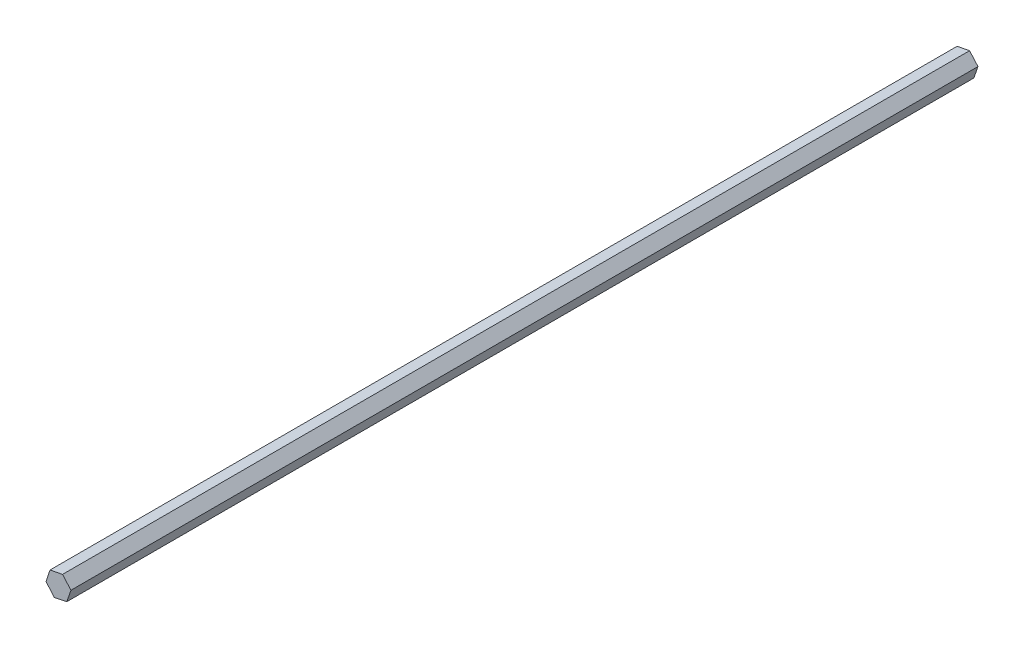
SolidWorks part; units mm, degrees
material "6061 Alloy"
ref_plane "Front Plane" through (0, 0, 0) normal (0, 0, 1) x (1, 0, 0)
ref_plane "Top Plane" through (0, 0, 0) normal (0, 1, 0) x (1, 0, 0)
ref_plane "Right Plane" through (0, 0, 0) normal (1, 0, 0) x (0, 0, -1)
ref_plane "Plane1" through (0, 0, -228.6) normal (0, 0, -1) x (-1, 0, 0)
sketch "Sketch1" plane through (0, 0, -228.6) normal (0, 0, -1) x (-1, 0, 0)
  line L0 (-2.3575, 6.9247) -> (-7.2099, 1.4275)
  line L1 (-7.2099, 1.4275) -> (-4.8182, -5.504)
  line L4 (-4.8182, -5.504) -> (2.3687, -6.9577)
  line L5 (2.3687, -6.9577) -> (7.1757, -1.4207)
  line L6 (7.1757, -1.4207) -> (4.8412, 5.5302)
  line L7 (4.8412, 5.5302) -> (-2.3575, 6.9247)
  circle A0 centre (0, 0) radius 6.35
  dimension "D1" = 12.7
extrude "Boss-Extrude1" add sketch "Sketch1" against normal blind 523.24
